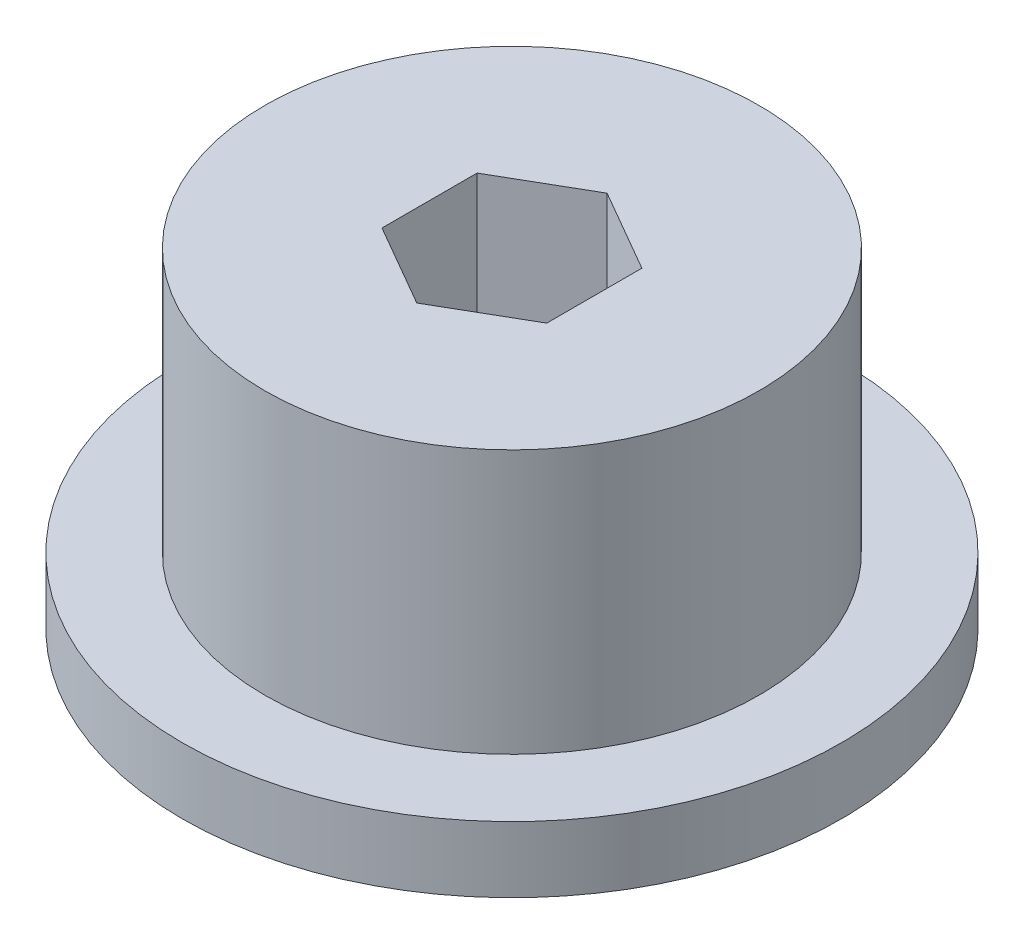
SolidWorks part; units mm, degrees
ref_plane "Front Plane" through (0, 0, 0) normal (0, 0, 1) x (1, 0, 0)
ref_plane "Top Plane" through (0, 0, 0) normal (0, 1, 0) x (1, 0, 0)
ref_plane "Right Plane" through (0, 0, 0) normal (1, 0, 0) x (0, 0, -1)
sketch "Sketch1" plane through (0, 0, 0) normal (0, 1, 0) x (1, 0, 0)
  circle A0 centre (0, 0) radius 10
  dimension "D1" = 20
extrude "Boss-Extrude1" add sketch "Sketch1" along normal blind 2
sketch "Sketch2" plane through (0, 2, 0) normal (0, 1, 0) x (1, 0, 0)
  circle A0 centre (0, 0) radius 7.5
  dimension "D1" = 15
extrude "Boss-Extrude2" add sketch "Sketch2" along normal blind 8
sketch "Sketch3" plane through (0, 10, 0) normal (0, 1, 0) x (1, 0, 0)
  line L1 (3.5, -1.4434) -> (3.5, 1.4434)
  line L2 (3.5, 1.4434) -> (1, 2.8868)
  line L3 (1, 2.8868) -> (-1.5, 1.4434)
  line L4 (-1.5, 1.4434) -> (-1.5, -1.4434)
  line L5 (-1.5, -1.4434) -> (1, -2.8868)
  line L6 (1, -2.8868) -> (3.5, -1.4434)
  circle A5 centre (1, 0) radius 2.5 construction
  dimension "D1" = 5
  dimension "D2" = 1
extrude "Cut-Extrude1" [suppressed] cut sketch "Sketch3" against normal up to next
sketch "Sketch4" plane through (0, 10, 0) normal (0, 1, 0) x (1, 0, 0)
  line L1 (2.5, 1.4434) -> (0, 2.8868)
  line L2 (0, 2.8868) -> (-2.5, 1.4434)
  line L3 (-2.5, 1.4434) -> (-2.5, -1.4434)
  line L4 (-2.5, -1.4434) -> (0, -2.8868)
  line L5 (0, -2.8868) -> (2.5, -1.4434)
  line L6 (2.5, -1.4434) -> (2.5, 1.4434)
  circle A4 centre (0, 0) radius 2.5 construction
  dimension "D1" = 5
extrude "Cut-Extrude2" cut sketch "Sketch4" against normal up to next
equation "\"R_ROLL\"= 5mm"
equation "\"D_SUN\"= 120mm"
equation "\"NUM_ROLL\"= 31"
equation "\"RHO\"= 1mm"
equation "\"D_SHAFT\"= 28mm"
equation "\"D_OUTPUT\"= 80mm"
equation "\"NUM_OUT\"= 8"
equation "\"R_OUT_ROLL\"= 5mm"
equation "\"D1@Sketch1\"=\"D_SHAFT\"-8"
equation "\"D2@Sketch3\"=\"RHO\""
